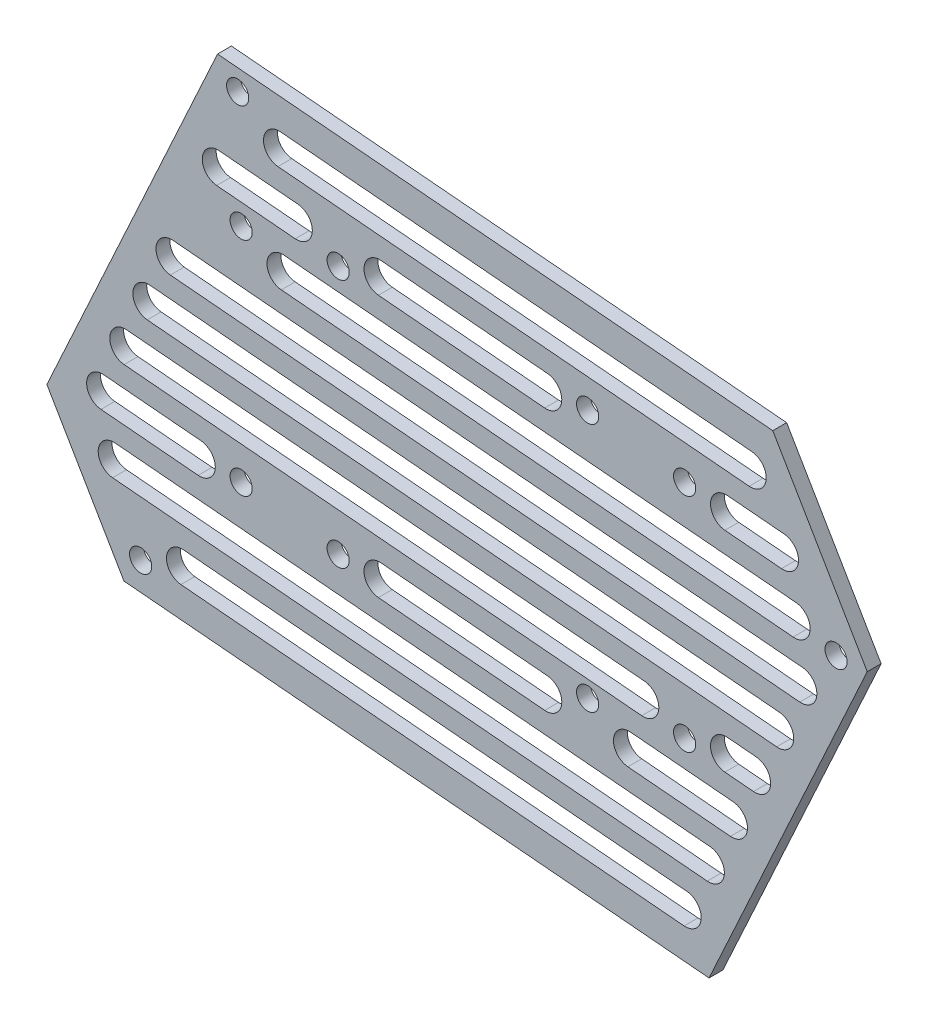
SolidWorks part; units mm, degrees
ref_plane "Front Plane" through (0, 0, 0) normal (0, 0, 1) x (1, 0, 0)
ref_plane "Top Plane" through (0, 0, 0) normal (0, 1, 0) x (1, 0, 0)
ref_plane "Right Plane" through (0, 0, 0) normal (1, 0, 0) x (0, 0, -1)
sketch "Sketch2" plane through (0, 0, 20) normal (0, 0, 1) x (1, 0, 0)
  line L0 (248.5642, 35.2708) -> (275.1174, 93.0694) construction
  line L1 (275.1174, 93.0694) -> (261.4848, 116.375) construction
  line L2 (261.4848, 116.375) -> (215.3421, 120.412) construction
  line L3 (252.2886, 43.3778) -> (275.1174, 93.0694)
  line L4 (275.1174, 93.0694) -> (261.4848, 116.375)
  line L5 (261.4848, 116.375) -> (181.3658, 123.3845)
  line L6 (181.3658, 123.3845) -> (156.7379, 69.7765)
  line L7 (156.7379, 69.7765) -> (167.859, 50.7644)
  line L8 (167.859, 50.7644) -> (252.2886, 43.3778)
  circle A0 centre (170.2676, 54.569) radius 1.25 construction
  circle A1 centre (184.2676, 120.1192) radius 1.25 construction
  circle A2 centre (184.2676, 120.1192) radius 1.6
  circle A3 centre (270.6134, 92.8471) radius 1.6
  circle A4 centre (170.2676, 54.569) radius 1.6
  dimension "D2" = 4
  dimension "D3" = 4
  dimension "D4" = 3.2
  dimension "D1" = 4
extrude "Boss-Extrude1" add sketch "Sketch2" along normal blind 2
sketch "Sketch3" plane through (0, 0, 22) normal (0, 0, 1) x (1, 0, 0)
  circle A0 centre (184.7676, 103.569) radius 1.6
  circle A1 centre (248.7676, 103.569) radius 1.6
  circle A2 centre (184.7676, 71.569) radius 1.6
  circle A3 centre (248.7676, 71.569) radius 1.6
  dimension "D1" = 3.2
extrude "Cut-Extrude1" cut sketch "Sketch3" against normal blind 10
sketch "Sketch4" plane through (0, 0, 22) normal (0, 0, 1) x (1, 0, 0)
  circle A0 centre (198.7677, 105.569) radius 1.6
  circle A1 centre (234.7676, 105.569) radius 1.6
  circle A2 centre (198.7677, 69.569) radius 1.6
  circle A3 centre (234.7676, 69.569) radius 1.6
  dimension "D1" = 3.2
extrude "Cut-Extrude2" cut sketch "Sketch4" against normal blind 10
sketch "Sketch5" plane through (0, 0, 22) normal (0, 0, 1) x (1, 0, 0)
  line L0 (190.2676, 115.9353) -> (258.271, 109.9858) construction
  line L1 (190.4655, 118.1967) -> (258.4689, 112.2472)
  line L2 (190.0698, 113.674) -> (258.0732, 107.7244)
  line L3 (181.4292, 109.1498) -> (192.7677, 108.1578) construction
  line L4 (181.627, 111.4112) -> (192.9655, 110.4192)
  line L5 (181.2313, 106.8885) -> (192.5698, 105.8965)
  line L6 (204.7677, 107.108) -> (228.7676, 105.0082) construction
  line L7 (204.9655, 109.3693) -> (228.9655, 107.2696)
  line L8 (204.5698, 104.8466) -> (228.5698, 102.7469)
  line L9 (254.7676, 102.7335) -> (262.931, 102.0193) construction
  line L13 (254.9655, 104.9949) -> (263.1289, 104.2807)
  line L14 (254.5698, 100.4722) -> (262.7332, 99.758)
  line L15 (190.7676, 100.7741) -> (264.6134, 94.3134) construction
  line L16 (190.9655, 103.0354) -> (264.8112, 96.5748)
  line L17 (190.5698, 98.5127) -> (264.4155, 92.052)
  line L18 (261.4848, 116.375) -> (181.3658, 123.3845) construction
  line L19 (174.7524, 94.6164) -> (265.5748, 86.6705) construction
  line L20 (174.9502, 96.8778) -> (265.7727, 88.9319)
  line L21 (174.5546, 92.3551) -> (265.377, 84.4091)
  line L22 (171.414, 87.3497) -> (262.2364, 79.4038) construction
  line L23 (171.6119, 89.6111) -> (262.4343, 81.6652)
  line L24 (171.2162, 85.0884) -> (262.0386, 77.1425)
  line L25 (168.0801, 80.0927) -> (242.7676, 73.5584) construction
  line L26 (168.2779, 82.3541) -> (242.9655, 75.8198)
  line L27 (167.8822, 77.8313) -> (242.5698, 71.297)
  line L28 (254.7676, 72.5085) -> (258.9025, 72.1468) construction
  line L29 (254.9655, 74.7699) -> (259.1003, 74.4081)
  line L30 (254.5698, 70.2472) -> (258.7046, 69.8854)
  line L31 (164.7417, 72.826) -> (178.7677, 71.5989) construction
  line L32 (164.9395, 75.0874) -> (178.9655, 73.8603)
  line L33 (164.5438, 70.5646) -> (178.5698, 69.3375)
  line L34 (204.7677, 69.3242) -> (228.7676, 67.2245) construction
  line L35 (204.9655, 71.5856) -> (228.9655, 69.4858)
  line L36 (204.5698, 67.0628) -> (228.5698, 64.9631)
  line L37 (240.7676, 66.1746) -> (255.5641, 64.8801) construction
  line L38 (240.9655, 68.436) -> (255.7619, 67.1414)
  line L39 (240.5698, 63.9132) -> (255.3663, 62.6187)
  line L40 (166.4122, 65.1211) -> (252.2257, 57.6134) construction
  line L41 (166.61, 67.3825) -> (252.4236, 59.8747)
  line L42 (166.2143, 62.8597) -> (252.0279, 55.352)
  line L43 (176.2676, 56.7001) -> (248.8873, 50.3467) construction
  line L44 (176.4655, 58.9615) -> (249.0852, 52.6081)
  line L45 (176.0698, 54.4387) -> (248.6895, 48.0853)
  line L48 (275.1174, 93.0694) -> (261.4848, 116.375) construction
  line L49 (252.2886, 43.3778) -> (275.1174, 93.0694) construction
  line L50 (156.7379, 69.7765) -> (167.859, 50.7644) construction
  line L51 (181.3658, 123.3845) -> (156.7379, 69.7765) construction
  arc A0 (190.4655, 118.1967) -> (190.0698, 113.674) centre (190.2676, 115.9353) ccw
  arc A1 (258.0732, 107.7244) -> (258.4689, 112.2472) centre (258.271, 109.9858) ccw
  arc A2 (181.627, 111.4112) -> (181.2313, 106.8885) centre (181.4292, 109.1498) ccw
  arc A3 (192.5698, 105.8965) -> (192.9655, 110.4192) centre (192.7677, 108.1578) ccw
  arc A4 (204.9655, 109.3693) -> (204.5698, 104.8466) centre (204.7677, 107.108) ccw
  arc A5 (228.5698, 102.7469) -> (228.9655, 107.2696) centre (228.7676, 105.0082) ccw
  arc A8 (254.9655, 104.9949) -> (254.5698, 100.4722) centre (254.7676, 102.7335) ccw
  arc A9 (262.7332, 99.758) -> (263.1289, 104.2807) centre (262.931, 102.0193) ccw
  arc A10 (190.9655, 103.0354) -> (190.5698, 98.5127) centre (190.7676, 100.7741) ccw
  arc A11 (264.4155, 92.052) -> (264.8112, 96.5748) centre (264.6134, 94.3134) ccw
  arc A12 (174.9502, 96.8778) -> (174.5546, 92.3551) centre (174.7524, 94.6164) ccw
  arc A13 (265.377, 84.4091) -> (265.7727, 88.9319) centre (265.5748, 86.6705) ccw
  arc A14 (171.6119, 89.6111) -> (171.2162, 85.0884) centre (171.414, 87.3497) ccw
  arc A15 (262.0386, 77.1425) -> (262.4343, 81.6652) centre (262.2364, 79.4038) ccw
  arc A16 (168.2779, 82.3541) -> (167.8822, 77.8313) centre (168.0801, 80.0927) ccw
  arc A17 (242.5698, 71.297) -> (242.9655, 75.8198) centre (242.7676, 73.5584) ccw
  arc A18 (254.9655, 74.7699) -> (254.5698, 70.2472) centre (254.7676, 72.5085) ccw
  arc A19 (258.7046, 69.8854) -> (259.1003, 74.4081) centre (258.9025, 72.1468) ccw
  arc A20 (164.9395, 75.0874) -> (164.5438, 70.5646) centre (164.7417, 72.826) ccw
  arc A21 (178.5698, 69.3375) -> (178.9655, 73.8603) centre (178.7677, 71.5989) ccw
  arc A22 (204.9655, 71.5856) -> (204.5698, 67.0628) centre (204.7677, 69.3242) ccw
  arc A23 (228.5698, 64.9631) -> (228.9655, 69.4858) centre (228.7676, 67.2245) ccw
  arc A24 (240.9655, 68.436) -> (240.5698, 63.9132) centre (240.7676, 66.1746) ccw
  arc A25 (255.3663, 62.6187) -> (255.7619, 67.1414) centre (255.5641, 64.8801) ccw
  arc A26 (166.61, 67.3825) -> (166.2143, 62.8597) centre (166.4122, 65.1211) ccw
  arc A27 (252.0279, 55.352) -> (252.4236, 59.8747) centre (252.2257, 57.6134) ccw
  arc A28 (176.4655, 58.9615) -> (176.0698, 54.4387) centre (176.2676, 56.7001) ccw
  arc A29 (248.6895, 48.0853) -> (249.0852, 52.6081) centre (248.8873, 50.3467) ccw
  circle A30 centre (184.2676, 120.1192) radius 1.6 construction
  circle A31 centre (198.7677, 105.569) radius 1.6 construction
  circle A32 centre (234.7676, 105.569) radius 1.6 construction
  circle A33 centre (248.7676, 103.569) radius 1.6 construction
  circle A34 centre (270.6134, 92.8471) radius 1.6 construction
  circle A35 centre (184.7676, 103.569) radius 1.6 construction
  circle A36 centre (184.7676, 71.569) radius 1.6 construction
  circle A37 centre (198.7677, 69.569) radius 1.6 construction
  circle A38 centre (234.7676, 69.569) radius 1.6 construction
  circle A39 centre (248.7676, 71.569) radius 1.6 construction
  circle A40 centre (170.2676, 54.569) radius 1.25 construction
  point P2 (224.2693, 112.9606)
  point P7 (187.0984, 108.6538)
  point P14 (216.7676, 106.0581)
  point P23 (258.8493, 102.3764)
  point P30 (227.6905, 97.5437)
  point P35 (220.1636, 90.6435)
  point P46 (216.8252, 83.3768)
  point P51 (267.8362, 86.4727)
  point P54 (205.4238, 76.8255)
  point P61 (256.835, 72.3277)
  point P66 (171.7547, 72.2125)
  point P73 (216.7676, 68.2743)
  point P80 (248.1659, 65.5273)
  point P87 (209.319, 61.3672)
  point P94 (212.5775, 53.5234)
  dimension "D1" = 2.27
  dimension "D27" = 6
  dimension "D28" = 6
  dimension "D29" = 6
  dimension "D30" = 6
  dimension "D31" = 6
  dimension "D32" = 6
  dimension "D33" = 6
  dimension "D34" = 6
  dimension "D35" = 6
  dimension "D36" = 6
  dimension "D37" = 6
  dimension "D38" = 6
  dimension "D2" = 7.53
  dimension "D3" = 7.53
  dimension "D4" = 7.53
  dimension "D5" = 7.53
  dimension "D6" = 7.52
  dimension "D7" = 7.53
  dimension "D8" = 7.53
  dimension "D9" = 7.53
  dimension "D10" = 4.375
  dimension "D11" = 6
  dimension "D12" = 6
  dimension "D13" = 6
  dimension "D14" = 6
  dimension "D15" = 6
  dimension "D16" = 6
  dimension "D17" = 6
  dimension "D18" = 6
  dimension "D19" = 6
  dimension "D20" = 6
  dimension "D21" = 6
  dimension "D22" = 6
  dimension "D23" = 6
  dimension "D24" = 6
  dimension "D25" = 6
  dimension "D26" = 6
extrude "Cut-Extrude3" cut sketch "Sketch5" against normal blind 10
